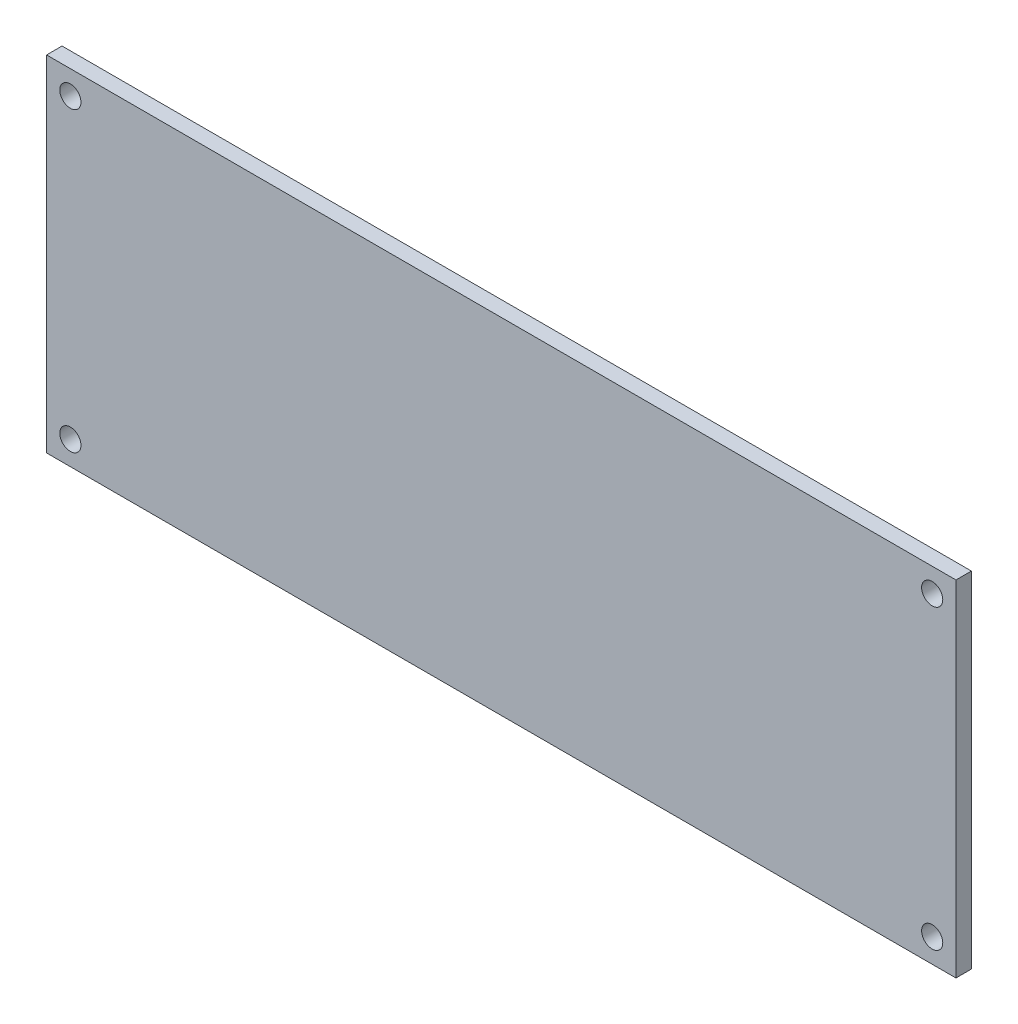
SolidWorks part; units mm, degrees
ref_plane "Front Plane" through (0, 0, 0) normal (0, 0, 1) x (1, 0, 0)
ref_plane "Top Plane" through (0, 0, 0) normal (0, 1, 0) x (1, 0, 0)
ref_plane "Right Plane" through (0, 0, 0) normal (1, 0, 0) x (0, 0, -1)
sketch "Sketch1" plane through (0, 0, 0) normal (0, 0, 1) x (1, 0, 0)
  line L1 (-48.5775, -18.415) -> (48.5775, -18.415)
  line L2 (-48.5775, -18.415) -> (-48.5775, 18.415)
  line L3 (-48.5775, 18.415) -> (48.5775, 18.415)
  line L4 (48.5775, -18.415) -> (48.5775, 18.415)
  line L5 (-48.5775, -18.415) -> (48.5775, 18.415) construction
  line L6 (-48.5775, 18.415) -> (48.5775, -18.415) construction
  point P0 (0, 0)
  dimension "D1" = 36.83
  dimension "D2" = 97.155
extrude "Boss-Extrude1" add sketch "Sketch1" along normal blind 1.651
hole_wizard "Tap Drill for #4-40 Tap1" positions "Sketch3" profile "Sketch2" hole size "#4-40" standard "ANSI Inch"
sketch "Sketch3" plane through (0, 0, 1.651) normal (0, 0, 1) x (1, 0, 0)
  line L18 (46.0375, -15.875) -> (46.0375, 15.875)
  line L19 (-46.0375, -15.875) -> (46.0375, -15.875)
  line L20 (-46.0375, 15.875) -> (-46.0375, -15.875)
  line L21 (46.0375, 15.875) -> (-46.0375, 15.875)
  line L22 (46.0375, -15.875) -> (46.0375, 15.875)
  line L23 (-46.0375, -15.875) -> (46.0375, -15.875)
  line L24 (-46.0375, 15.875) -> (-46.0375, -15.875)
  line L25 (46.0375, 15.875) -> (-46.0375, 15.875)
  point P0 (-46.0375, 15.875)
  point P2 (-46.0375, -15.875)
  point P4 (46.0375, -15.875)
  point P6 (46.0375, 15.875)
  dimension "D1" = 2.54
sketch "Sketch2" plane through (-46.0375, 15.875, 1.651) normal (1, 0, 0) x (0, -1, 0)
  line L0 (0, 0) -> (0, 12.7)
  line L1 (0, 12.7) -> (1.1303, 12.7)
  line L2 (1.1303, 12.7) -> (1.1303, 0)
  line L5 (1.1303, 0) -> (0, 0)
  line L10 (0, 12.7) -> (-1.1303, 12.7) construction
  line L11 (0, -6.35) -> (0, 107.95) construction
  dimension "Hole Dia." = 2.2606
  dimension "Hole Depth" = 12.7
  dimension "Drill Angle" = 180
